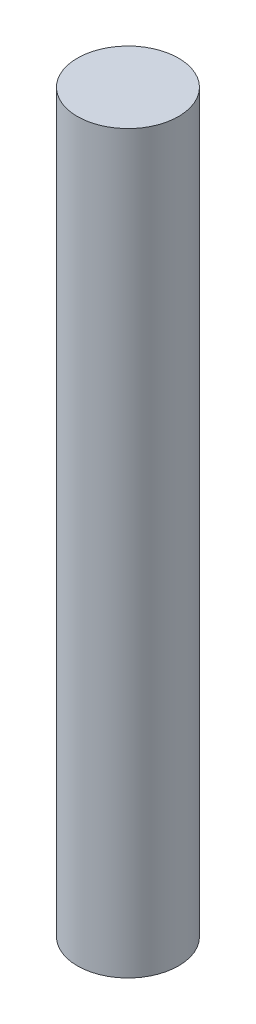
SolidWorks part; units mm, degrees
ref_plane "前视基准面" through (0, 0, 0) normal (0, 0, 1) x (1, 0, 0)
ref_plane "上视基准面" through (0, 0, 0) normal (0, 1, 0) x (1, 0, 0)
ref_plane "右视基准面" through (0, 0, 0) normal (1, 0, 0) x (0, 0, -1)
other "Configuration Table"
sketch "草图1" plane through (0, 0, 0) normal (0, 1, 0) x (1, 0, 0)
  circle A0 centre (0, 0) radius 6
  dimension "D1" = 12
extrude "凸台-拉伸1" add sketch "草图1" along normal mid plane 87.26
